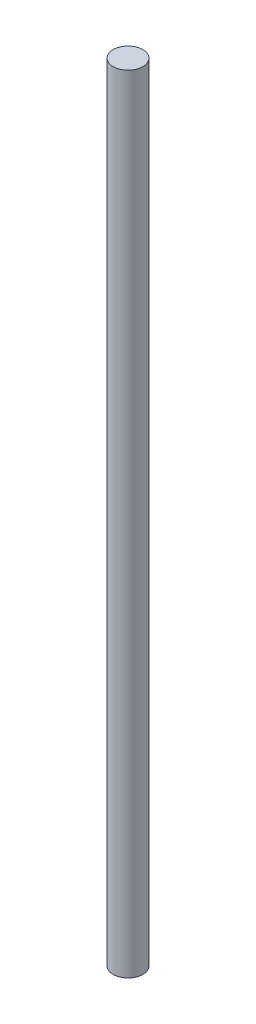
SolidWorks part; units mm, degrees
material "1060 合金"
ref_plane "前视基准面" through (0, 0, 0) normal (0, 0, 1) x (1, 0, 0)
ref_plane "上视基准面" through (0, 0, 0) normal (0, 1, 0) x (1, 0, 0)
ref_plane "右视基准面" through (0, 0, 0) normal (1, 0, 0) x (0, 0, -1)
other "Configuration Table"
sketch "草图1" plane through (0, 0, 0) normal (0, 1, 0) x (1, 0, 0)
  circle A0 centre (0, 0) radius 1
  dimension "D1" = 2
extrude "凸台-拉伸1" add sketch "草图1" along normal blind 53
